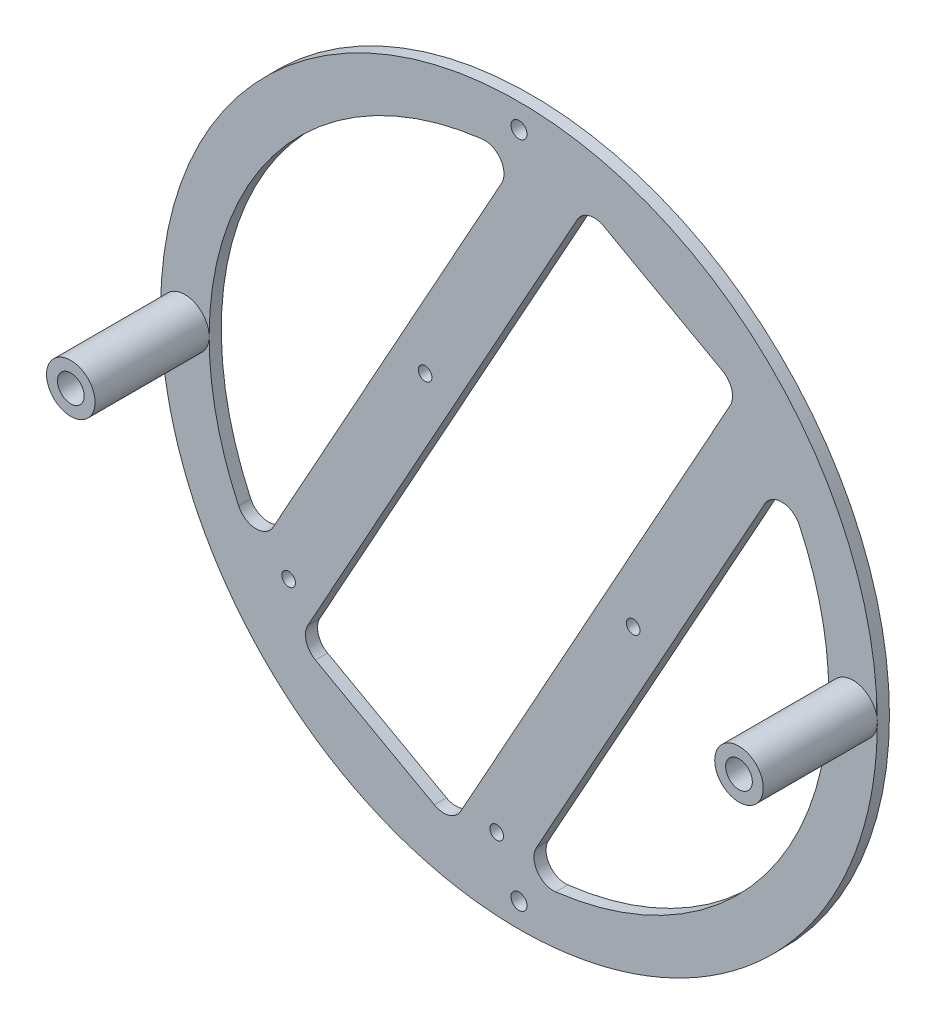
SolidWorks part; units mm, degrees
material "PETG"
ref_plane "Front Plane" through (0, 0, 0) normal (0, 0, 1) x (1, 0, 0)
ref_plane "Top Plane" through (0, 0, 0) normal (0, 1, 0) x (1, 0, 0)
ref_plane "Right Plane" through (0, 0, 0) normal (1, 0, 0) x (0, 0, -1)
sketch "Sketch1" plane through (0, 0, 0) normal (0, 0, 1) x (1, 0, 0)
  line L0 (-76.2, 0) -> (76.2, 0) construction
  line L1 (0, 76.2) -> (0, -76.2) construction
  line L12 (-3.2307, -63.583) -> (-52.2094, -36.4336) construction
  line L17 (-52.2094, -36.4336) -> (-9.5462, 40.5329) construction
  line L18 (19.7536, 24.2918) -> (11.2694, 8.9859) construction
  line L19 (39.4325, 13.3836) -> (-3.2307, -63.583) construction
  line L24 (-27.7201, -50.0083) -> (14.9432, 26.9582) construction
  line L25 (-7.4471, 39.3694) -> (8.5827, 68.2878) construction
  line L26 (-4.595, -58.825) -> (-47.4514, -35.0693) construction
  line L27 (-47.4514, -35.0693) -> (-19.3324, 15.6586) construction
  line L31 (-19.3324, 15.6586) -> (23.5239, -8.097) construction
  line L32 (23.5239, -8.097) -> (-4.595, -58.825) construction
  line L33 (37.5958, 14.4017) -> (27.1724, -4.4027) construction
  line L34 (27.1724, -4.4027) -> (13.0036, 3.4513) construction
  line L35 (13.0036, 3.4513) -> (23.427, 22.2556) construction
  line L36 (23.427, 22.2556) -> (37.5958, 14.4017) construction
  line L37 (11.2694, 8.9859) -> (-0.2755, 15.3854) construction
  line L38 (-0.2755, 15.3854) -> (8.2086, 30.6913) construction
  line L39 (-10, -41.35) -> (10, -41.35) construction
  line L40 (10, -37.25) -> (-10, -37.25) construction
  line L41 (-41.85, -8.75) -> (-41.85, 8.75) construction
  line L51 (8.2086, 30.6913) -> (19.7536, 24.2918) construction
  line L55 (-37.75, 8.75) -> (-37.75, -8.75) construction
  line L56 (37.75, 8.75) -> (37.75, -8.75) construction
  line L57 (41.85, -8.75) -> (41.85, 8.75) construction
  line L58 (4.0979, 32.9699) -> (-4.3863, 17.664) construction
  line L65 (-4.3863, 17.664) -> (-15.9312, 24.0635) construction
  line L66 (-15.9312, 24.0635) -> (-7.4471, 39.3694) construction
  line L67 (4.0979, 32.9699) -> (-7.4471, 39.3694) construction
  line L68 (39.4325, 13.3836) -> (-9.5462, 40.5329) construction
  line L69 (-1.9941, -56.608) -> (-8.5538, -52.9719) construction
  line L70 (-8.5538, -52.9719) -> (-4.1905, -45.1003) construction
  line L71 (-4.1905, -45.1003) -> (2.3692, -48.7364) construction
  line L72 (2.3692, -48.7364) -> (-1.9941, -56.608) construction
  line L73 (37.5958, 14.4017) -> (53.5669, 43.2142) construction
  line L74 (-0.0652, 63.825) -> (-54.1612, -33.7668)
  line L75 (0.0652, -63.825) -> (54.1612, 33.7668)
  line L76 (-45.4301, -44.8301) -> (13.9438, 62.2832)
  line L77 (45.4301, 44.8301) -> (-13.9438, -62.2832)
  line L78 (-45.4301, -44.8301) -> (-13.9438, -62.2832)
  line L79 (13.9438, 62.2832) -> (45.4301, 44.8301)
  circle A0 centre (0, 0) radius 76.2 construction
  circle A1 centre (0, 0) radius 68.825 construction
  circle A2 centre (0, 79.35) radius 1.65 construction
  circle A3 centre (46.6408, 64.1955) radius 1.65 construction
  circle A4 centre (75.4663, 24.5205) radius 1.65 construction
  circle A5 centre (75.4663, -24.5205) radius 1.65 construction
  circle A6 centre (46.6408, -64.1955) radius 1.65 construction
  circle A7 centre (0, -79.35) radius 1.65 construction
  circle A8 centre (-46.6408, -64.1955) radius 1.65 construction
  circle A9 centre (-75.4663, -24.5205) radius 1.65 construction
  circle A10 centre (-75.4663, 24.5205) radius 1.65 construction
  circle A11 centre (-46.6408, 64.1955) radius 1.65 construction
  circle A15 centre (0, 0) radius 73.825
  circle A16 centre (0, 0) radius 63.825 construction
  circle A19 centre (0, 68.825) radius 1.65
  circle A20 centre (68.825, 0) radius 1.65
  circle A21 centre (0, -68.825) radius 1.65
  circle A22 centre (-68.825, 0) radius 1.65
  circle A29 centre (0, 68.825) radius 2.7 construction
  circle A30 centre (68.825, 0) radius 2.7 construction
  circle A31 centre (0, -68.825) radius 2.7 construction
  circle A32 centre (-68.825, 0) radius 2.7 construction
  arc A37 (10, -41.35) -> (10, -37.25) centre (10, -39.3) ccw construction
  arc A38 (-10, -37.25) -> (-10, -41.35) centre (-10, -39.3) ccw construction
  arc A39 (-41.85, 8.75) -> (-37.75, 8.75) centre (-39.8, 8.75) cw construction
  arc A40 (-37.75, -8.75) -> (-41.85, -8.75) centre (-39.8, -8.75) cw construction
  arc A41 (41.85, 8.75) -> (37.75, 8.75) centre (39.8, 8.75) ccw construction
  arc A42 (37.75, -8.75) -> (41.85, -8.75) centre (39.8, -8.75) ccw construction
  circle A43 centre (-4.595, -58.825) radius 1.4
  circle A44 centre (-47.4514, -35.0693) radius 1.4
  circle A45 centre (-19.3324, 15.6586) radius 1.4
  circle A46 centre (23.5239, -8.097) radius 1.4
  arc A47 (0.0652, -63.825) -> (54.1612, 33.7668) centre (0, 0) ccw
  arc A49 (-54.1612, -33.7668) -> (-0.0652, 63.825) centre (0, 0) cw
  point P26 (0, 0)
  point P44 (0, 0)
  point P50 (0, 0)
  point P68 (30.5114, 18.3286)
  point P84 (13.9811, 27.4915)
  point P86 (0, 0)
  point P92 (-1.6746, 36.1696)
  point P95 (0.1875, -52.6722)
  point P96 (0, -41.35)
  point P102 (-37.75, 0)
  dimension "D1" = 152.4
  dimension "D2" = 137.65
  dimension "D6" = 3.3
  dimension "D7" = 4
  dimension "D8" = 56
  dimension "D11" = 88
  dimension "D12" = 2.8
  dimension "D13" = 24.5
  dimension "D15" = 49
  dimension "D14" = 3.5
  dimension "D24" = 5.4
  dimension "D4" = 79.35
  dimension "D16" = 58
  dimension "D17" = 21.5
  dimension "D18" = 16.2
  dimension "D19" = 10.2
  dimension "D20" = 17.5
  dimension "D21" = 20
  dimension "D22" = 4.1
  dimension "D23" = 4.1
  dimension "D26" = 13.2
  dimension "D27" = 29.1
  dimension "D28" = 47
  dimension "D29" = 11.2
  dimension "D30" = 9
  dimension "D31" = 7.5
  dimension "D32" = 1.2
  dimension "D33" = 29
  dimension "D34" = 6.5
  dimension "D35" = 6.5
  dimension "D36" = 13
  dimension "D37" = 13
  dimension "D38" = 5
  dimension "D39" = 37.25
  dimension "D40" = 17.5
  dimension "D41" = 37.75
  dimension "D9" = 5
  dimension "D10" = 5
  dimension "D5" = 10
  dimension "D25" = 4
other "AlignGroup1"
extrude "Boss-Extrude1" add sketch "Sketch1" along normal blind 2.5
fillet "Fillet1" radius 4 8 edges at (-13.9438, -62.2832, 1.25) (-45.4301, -44.8301, 1.25) (45.4301, 44.8301, 1.25) (13.9438, 62.2832, 1.25) (54.1612, 33.7668, 1.25) (0.0652, -63.825, 1.25) (-0.0652, 63.825, 1.25) (-54.1612, -33.7668, 1.25)
sketch "Sketch2" plane through (0, 0, 2.5) normal (0, 0, 1) x (1, 0, 0)
  line L3 (0, 68.825) -> (0, -68.825) construction
  circle A7 centre (68.825, 0) radius 1.65 construction
  circle A9 centre (68.825, 0) radius 1.65 construction
  circle A10 centre (-68.825, 0) radius 5
  circle A11 centre (68.825, 0) radius 5
  circle A12 centre (0, 0) radius 73.825 construction
  circle A13 centre (-68.825, 0) radius 2.75
  circle A14 centre (-68.825, 0) radius 1.65 construction
  circle A15 centre (-68.825, 0) radius 1.65 construction
  circle A16 centre (68.825, 0) radius 2.75
  dimension "D1" = 5.5
extrude "Boss-Extrude2" add sketch "Sketch2" along normal blind 23.5
fillet "Fillet2" [suppressed] radius 1
